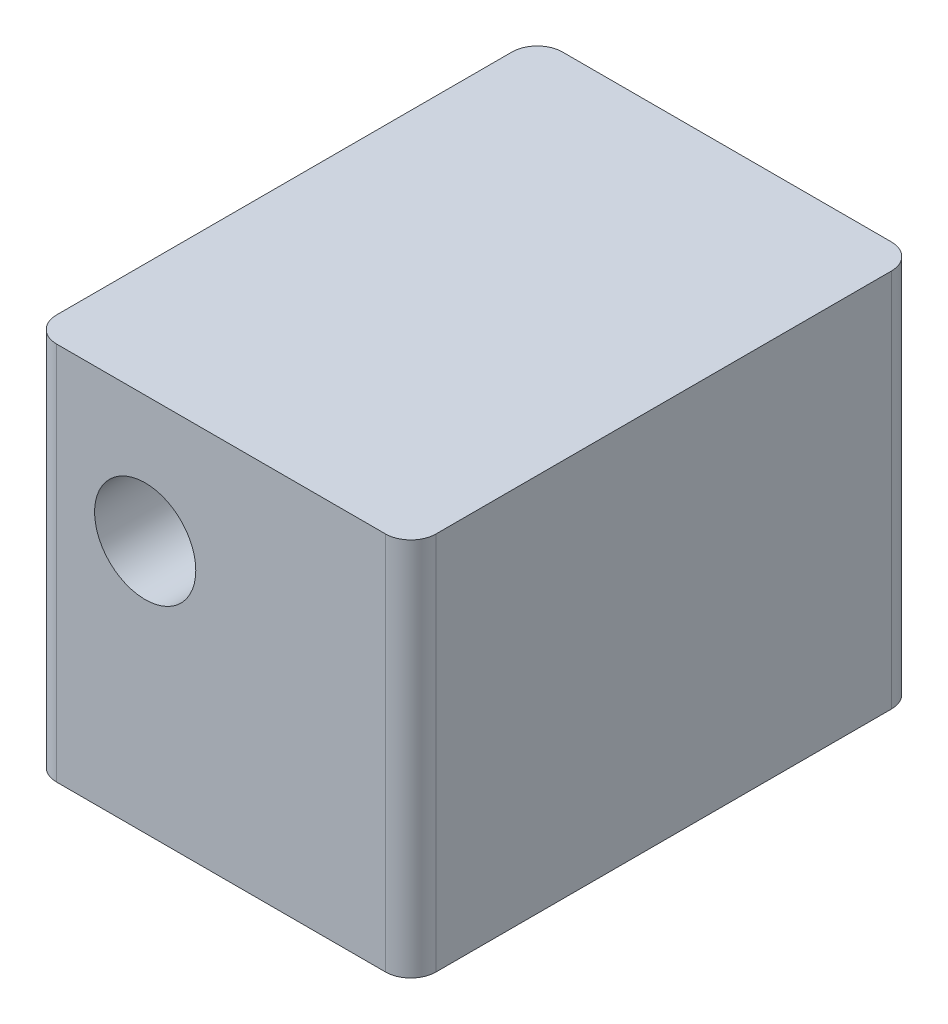
SolidWorks part; units mm, degrees
ref_plane "Plan de face" through (0, 0, 0) normal (0, 0, 1) x (1, 0, 0)
ref_plane "Plan de dessus" through (0, 0, 0) normal (0, 1, 0) x (1, 0, 0)
ref_plane "Plan de droite" through (0, 0, 0) normal (1, 0, 0) x (0, 0, -1)
sketch "Esquisse1" plane through (0, 0, 0) normal (0, 1, 0) x (1, 0, 0)
  line L0 (0, 0) -> (7.5, 0)
  line L1 (0, 0) -> (-7.5, 0)
  line L2 (-7.5, 0) -> (-7.5, 20)
  line L3 (-7.5, 20) -> (7.5, 20)
  line L4 (7.5, 20) -> (7.5, 0)
  dimension "D1" = 20
  dimension "D2" = 15
extrude "Boss.-Extru.1" add sketch "Esquisse1" along normal blind 15
sketch "Esquisse2" plane through (0, 0, 0) normal (0, -1, 0) x (1, 0, 0)
  line L0 (-7.5, -20) -> (-7.5, -16) construction
  line L1 (-7.5, -20) -> (-7.5, 0) construction
  line L2 (-7.5, -16) -> (1.5, -16) construction
  line L3 (7.5, 0) -> (7.5, -4) construction
  line L4 (7.5, 0) -> (7.5, -20) construction
  line L6 (7.5, -4) -> (-1.5, -4) construction
  circle A3 centre (-3, -16) radius 2
  circle A4 centre (3, -4) radius 2
  dimension "D2" = 9
  dimension "D1" = 4
  dimension "D3" = 4
  dimension "D4" = 9
extrude "Enlèv. mat.-Extru.1" cut sketch "Esquisse2" against normal blind 12
sketch "Esquisse3" plane through (0, 0, 0) normal (0, 0, 1) x (1, 0, 0)
  line L0 (0, 0) -> (-3, 0) construction
  line L1 (-7.5, 0) -> (7.5, 0) construction
  line L2 (-3, 0) -> (-3, 10) construction
  circle A1 centre (-3, 10) radius 2
  dimension "D1" = 10
  dimension "D2" = 3
extrude "Enlèv. mat.-Extru.2" cut sketch "Esquisse3" against normal blind 12
fillet "Congé1" radius 1 4 edges at (7.5, 7.5, -20) (-7.5, 7.5, -20) (-7.5, 7.5, 0) (7.5, 7.5, 0)
